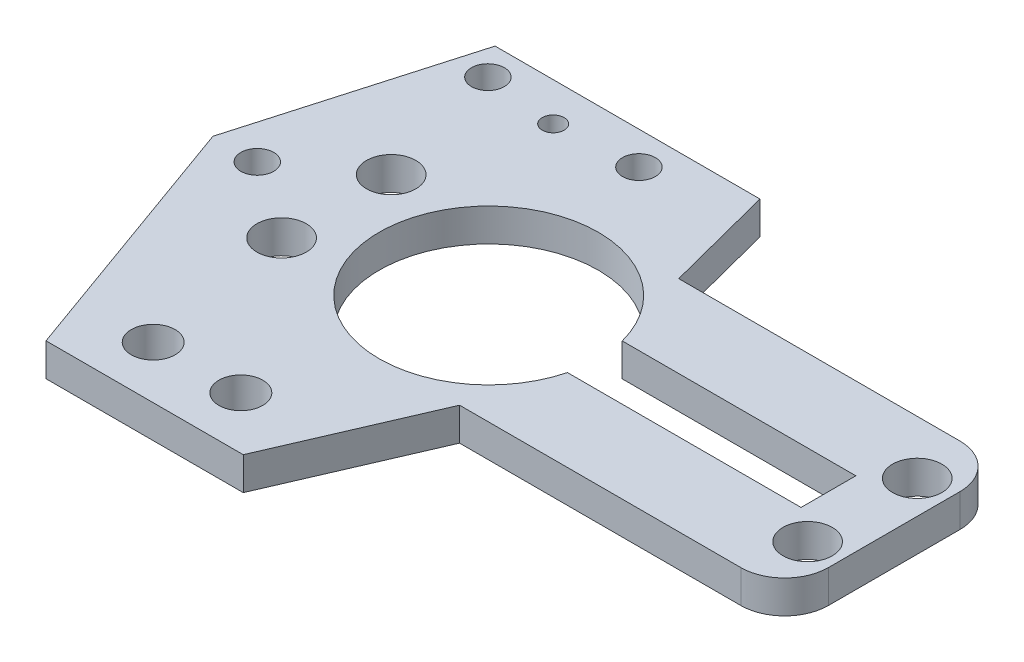
SolidWorks part; units mm, degrees
ref_plane "前视基准面" through (0, 0, 0) normal (0, 0, 1) x (1, 0, 0)
ref_plane "上视基准面" through (0, 0, 0) normal (0, 1, 0) x (1, 0, 0)
ref_plane "右视基准面" through (0, 0, 0) normal (1, 0, 0) x (0, 0, -1)
sketch "草图1" plane through (0, 0, 0) normal (0, 1, 0) x (1, 0, 0)
  line L0 (-56.5102, 0) -> (56.5102, 0) construction
  line L1 (0, 43.7755) -> (0, -43.7755) construction
  line L3 (-9, -23.7803) -> (-17.5475, 0)
  line L4 (-17.5475, 0) -> (-11.8002, 20)
  line L6 (12.3674, 20) -> (14.9564, 10)
  line L7 (14.9564, 10) -> (44.6177, 10)
  line L8 (44.6177, 10) -> (44.6177, -10)
  line L9 (44.6177, -10) -> (14.9564, -10)
  line L10 (14.9564, -10) -> (9, -23.7803)
  line L12 (11.636, 0) -> (-46.731, 0) construction
  line L13 (-9, -23.7803) -> (9, -23.7803)
  line L15 (17.3001, -2.5) -> (38.6177, -2.5)
  line L16 (38.6177, -2.5) -> (38.6177, 2.5)
  line L17 (38.6177, 2.5) -> (17.3001, 2.5)
  line L18 (-11.8002, 20) -> (12.3674, 20)
  line L19 (7.6177, 0) -> (-13.5, 0) construction
  line L20 (5.9403, -198.1527) -> (5.9403, -146.5632) construction
  line L21 (-3.3994, -29.7967) -> (-2.4781, 29.7967) construction
  circle A2 centre (-4, -19) radius 2
  circle A3 centre (4, -19) radius 2
  circle A7 centre (-3, 16.5) radius 1
  arc A9 (17.3001, 2.5) -> (17.3001, -2.5) centre (7.6177, 0) ccw
  circle A10 centre (4.3249, 17) radius 1.5
  circle A11 centre (41.6177, 5.1) radius 2.25
  circle A12 centre (41.6177, -4.9) radius 2.25
  circle A13 centre (-6.3823, -4.9) radius 2.25
  circle A14 centre (-6.3823, 5.1) radius 2.25
  circle A15 centre (-13.5, 0) radius 1.5
  circle A16 centre (-9.6734, 17.2164) radius 1.5
  point P4 (0, 0)
  point P8 (0, 0)
  point P29 (-17.5475, 0)
  point P40 (0, 0)
  point P47 (5.9403, -172.358)
  point P51 (-2.9387, 0)
  point P52 (-2.213, 16.54)
  dimension "D3" = 4
  dimension "D4" = 20
  dimension "D2" = 3
  dimension "D12" = 3
  dimension "D14" = 3
  dimension "2" = 2
  dimension "D16" = 4.5
  dimension "D1" = 18
  dimension "D5" = 19
  dimension "D6" = 8
  dimension "D7" = 20
  dimension "D8" = 5
  dimension "D9" = 6
  dimension "D10" = 3
  dimension "D11" = 14
  dimension "D13" = 13.5
  dimension "D15" = 3.5
  dimension "D17" = 7.6177
  dimension "D18" = 10.56
extrude "凸台-拉伸1" add sketch "草图1" along normal blind 3
fillet "圆角1" radius 4 2 edges at (44.6177, 1.5, 10) (44.6177, 1.5, -10)
